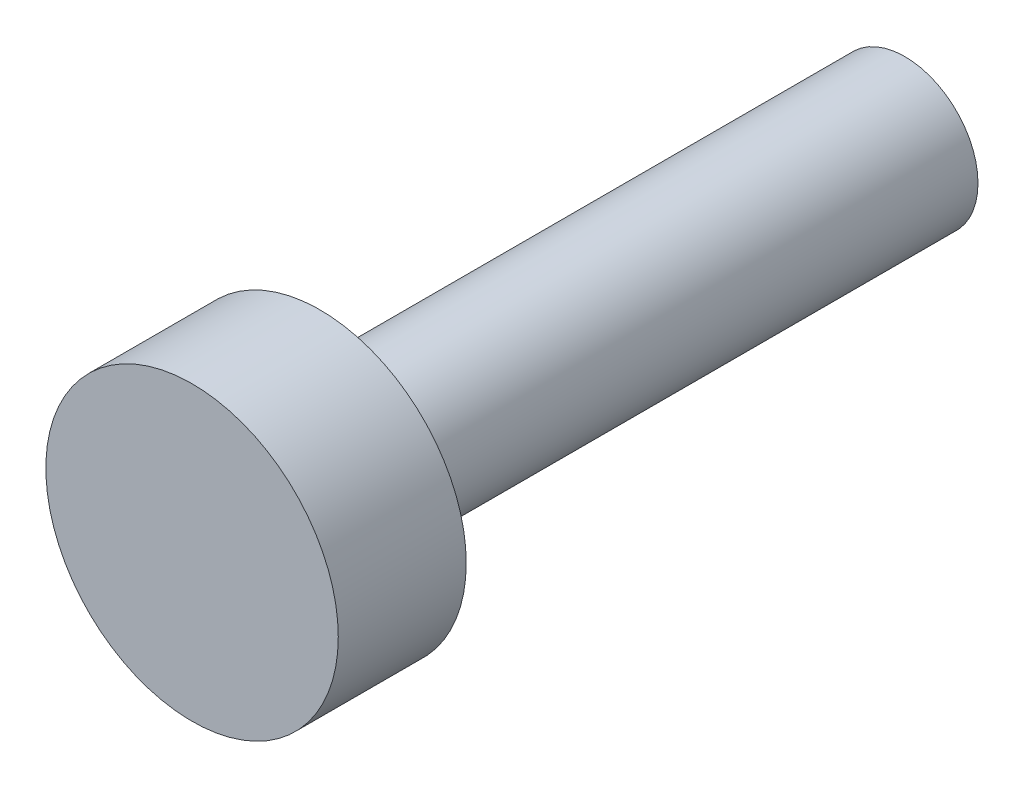
SolidWorks part; units mm, degrees
ref_plane "Спереди" through (0, 0, 0) normal (0, 0, 1) x (1, 0, 0)
ref_plane "Сверху" through (0, 0, 0) normal (0, 1, 0) x (1, 0, 0)
ref_plane "Справа" through (0, 0, 0) normal (1, 0, 0) x (0, 0, -1)
sketch "Эскиз1" plane through (0, 0, 0) normal (0, 0, 1) x (1, 0, 0)
  circle A0 centre (0, 0) radius 2
  dimension "D1" = 4
extrude "Бобышка-Вытянуть1" add sketch "Эскиз1" along normal blind 16
sketch "Эскиз2" plane through (0, 0, 16) normal (0, 0, 1) x (1, 0, 0)
  circle A0 centre (0, 0) radius 4
  dimension "D1" = 8
extrude "Бобышка-Вытянуть2" add sketch "Эскиз2" along normal blind 3.5
